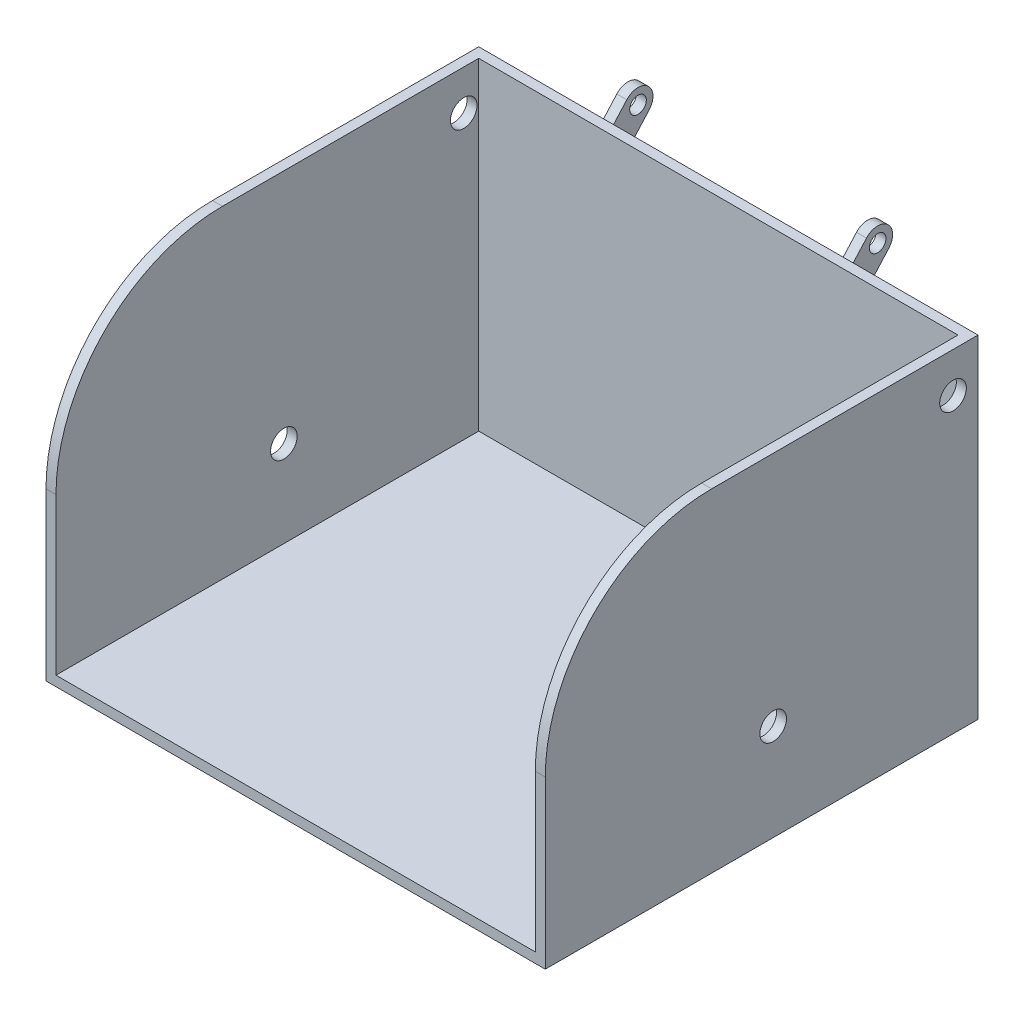
SolidWorks part; units mm, degrees
ref_plane "Front Plane" through (0, 0, 0) normal (0, 0, 1) x (1, 0, 0)
ref_plane "Top Plane" through (0, 0, 0) normal (0, 1, 0) x (1, 0, 0)
ref_plane "Right Plane" through (0, 0, 0) normal (1, 0, 0) x (0, 0, -1)
sketch "Sketch1" plane through (0, 0, 0) normal (1, 0, 0) x (0, 0, -1)
  line L0 (0, 0) -> (-130, 0)
  line L1 (-130, 0) -> (-130, 50)
  line L2 (-80, 100) -> (0, 100)
  line L3 (0, 100) -> (0, 0)
  arc A0 (-130, 50) -> (-80, 100) centre (-80, 50) cw
  dimension "D1" = 130
  dimension "D2" = 100
  dimension "D3" = 50
extrude "Boss-Extrude1" add sketch "Sketch1" along normal blind 150 contours A0 L2 L3 L0 L1
sketch "Sketch2" plane through (0, 100, 0) normal (0, 1, 0) x (1, 0, 0)
  line L0 (150, 0) -> (0, 0) construction
  line L1 (3, -3) -> (147, -3)
  line L2 (3, -3) -> (3, -135)
  line L3 (3, -135) -> (147, -135)
  line L4 (147, -3) -> (147, -135)
  line L5 (150, -80) -> (150, 0) construction
  line L6 (0, -80) -> (0, 0) construction
  line L8 (150, -130) -> (0, -130) construction
  dimension "D1" = 3
  dimension "D2" = 3
  dimension "D3" = 3
  dimension "D4" = 5
extrude "Cut-Extrude1" cut sketch "Sketch2" against normal offset from surface (97 mm away) 3 up to face at (75, 0, 65)
ref_plane "Plane1" through (75, 0, 0) normal (1, 0, 0) x (0, 0, -1)
ref_plane "Plane2" through (111, 0, 0) normal (1, 0, 0) x (0, 0, -1)
ref_plane "Plane3" through (39, 0, 0) normal (1, 0, 0) x (0, 0, -1)
sketch "Sketch3" plane through (111, 0, 0) normal (1, 0, 0) x (0, 0, -1)
  line L0 (0, 100) -> (0, 86.4837)
  line L1 (0, 86.4837) -> (10.7098, 98.4837)
  line L2 (3.9952, 104.4764) -> (0, 100)
  arc A0 (10.7098, 98.4837) -> (3.9952, 104.4764) centre (7.3525, 101.4801) ccw
  circle A1 centre (7.3525, 101.4801) radius 2.5
  dimension "D1" = 2
  dimension "D2" = 5
  dimension "D3" = 6
  dimension "D4" = 12
extrude "Boss-Extrude2" add sketch "Sketch3" along normal mid plane 3
mirror "Mirror1" about plane through (75, 0, 0) normal (1, 0, 0) of "Boss-Extrude2"
sketch "Sketch4" plane through (150, 0, 0) normal (1, 0, 0) x (0, 0, -1)
  line L0 (-7.5037, 88) -> (-61.5315, 29) construction
  line L1 (0, 0) -> (-130, 0) construction
  line L2 (-80, 100) -> (0, 100) construction
  circle A0 centre (-61.5315, 29) radius 4
  circle A1 centre (-7.5037, 88) radius 4
  dimension "D4" = 8
  dimension "D5" = 8
  dimension "D1" = 80
  dimension "D2" = 29
  dimension "D3" = 12
extrude "Cut-Extrude2" cut sketch "Sketch4" against normal up to next
mirror "Mirror2" about plane through (75, 0, 0) normal (1, 0, 0) of "Cut-Extrude2"
equation "\"forward_length\"= 130"
equation "\"height\"= 100"
equation "\"eslabon_AB\"=80"
